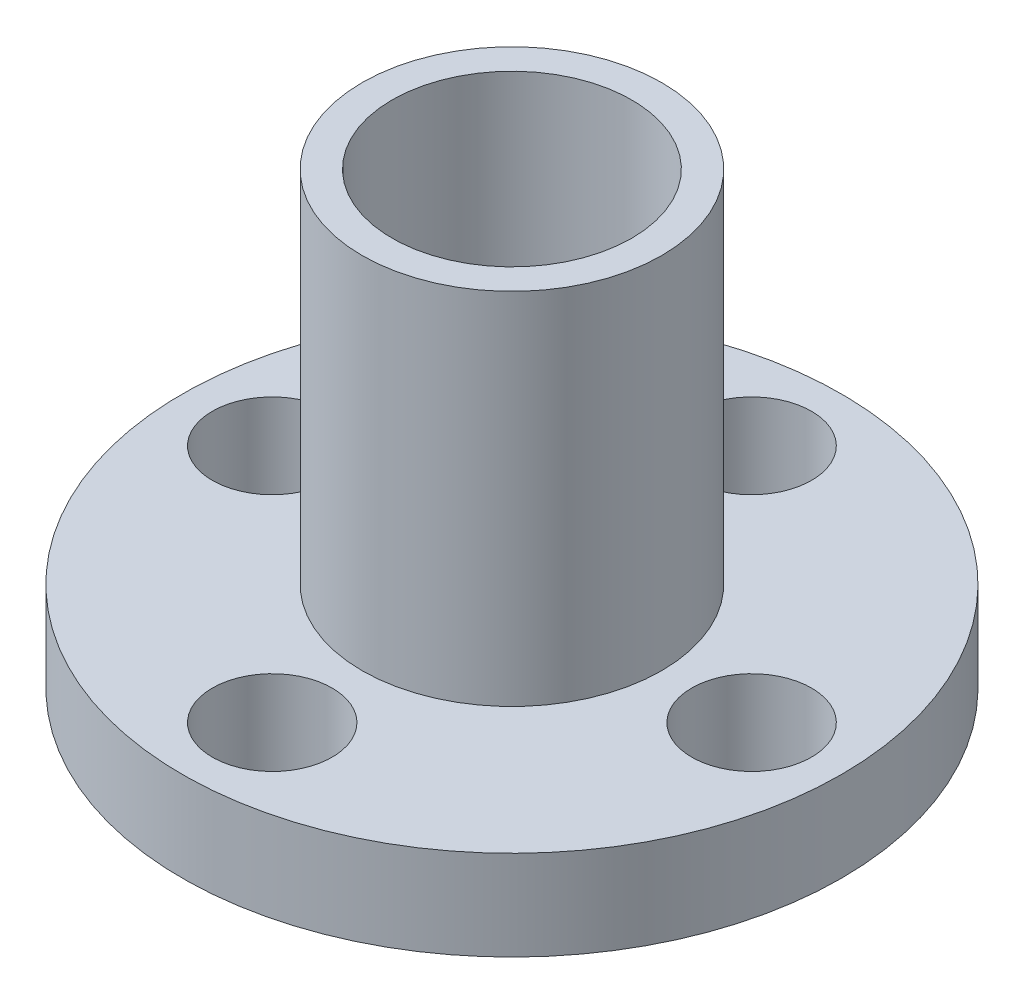
SolidWorks part; units mm, degrees
ref_plane "Front Plane" through (0, 0, 0) normal (0, 0, 1) x (1, 0, 0)
ref_plane "Top Plane" through (0, 0, 0) normal (0, 1, 0) x (1, 0, 0)
ref_plane "Right Plane" through (0, 0, 0) normal (1, 0, 0) x (0, 0, -1)
sketch "Sketch1" plane through (0, 0, 0) normal (0, 0, 1) x (1, 0, 0)
  line L0 (-4, 0) -> (-11, 0)
  line L1 (-11, 0) -> (-11, 3)
  line L2 (-11, 3) -> (-5, 3)
  line L3 (-5, 3) -> (-5, 15)
  line L4 (-5, 15) -> (-4, 15)
  line L5 (-4, 15) -> (-4, 0)
  line L6 (0, -177.2018) -> (0, 8682.8871) construction
  dimension "D1" = 15
  dimension "D2" = 11
  dimension "D3" = 5
  dimension "D4" = 4
  dimension "D5" = 3
revolve "Revolve1" add sketch "Sketch1" angle 360 about L6
sketch "Sketch2" plane through (0, 3, 0) normal (0, 1, 0) x (1, 0, 0)
  circle A0 centre (0, 8) radius 2
  circle A1 centre (8, 0) radius 2
  circle A2 centre (0, -8) radius 2
  circle A3 centre (-8, 0) radius 2
  point P12 (0, 0)
  dimension "D1" = 4
  dimension "D2" = 8
  dimension "D3" = 4
extrude "Cut-Extrude1" cut sketch "Sketch2" against normal through all
